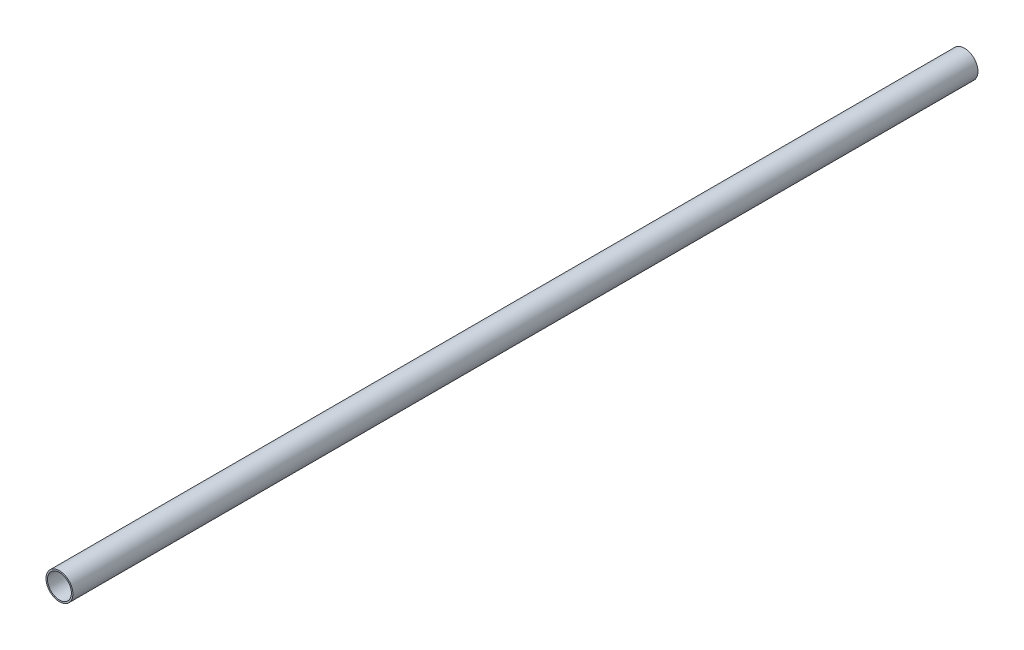
SolidWorks part; units mm, degrees
material "AISI 4130 Steel, annealed at 865C"
ref_plane "Front Plane" through (0, 0, 0) normal (0, 0, 1) x (1, 0, 0)
ref_plane "Top Plane" through (0, 0, 0) normal (0, 1, 0) x (1, 0, 0)
ref_plane "Right Plane" through (0, 0, 0) normal (1, 0, 0) x (0, 0, -1)
sketch "Sketch1" plane through (0, 0, 0) normal (0, 0, 1) x (1, 0, 0)
  circle A0 centre (0, 0) radius 7.9375
  circle A1 centre (0, 0) radius 7.0485
  dimension "D1" = 15.875
  dimension "D2" = 0.889
extrude "Boss-Extrude1" add sketch "Sketch1" along normal blind 533.4
